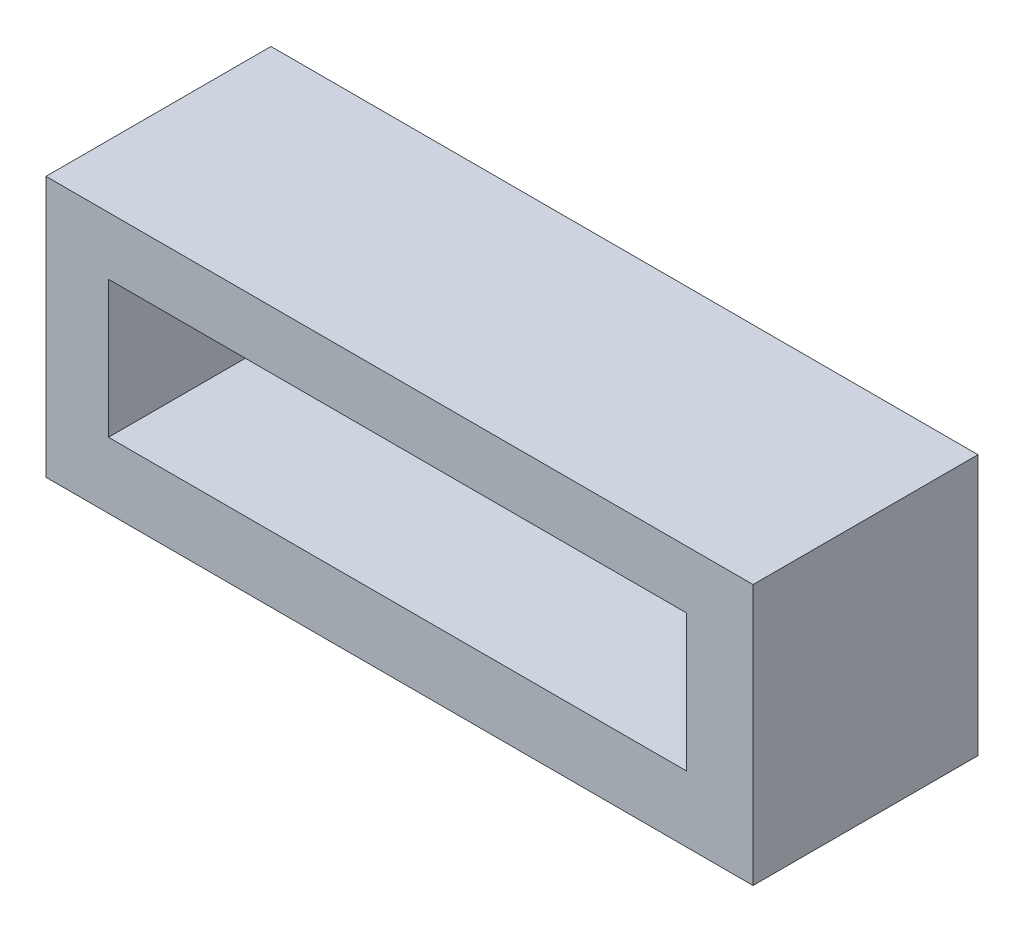
SolidWorks part; units mm, degrees
ref_plane "前基準面" through (0, 0, 0) normal (0, 0, 1) x (1, 0, 0)
ref_plane "上基準面" through (0, 0, 0) normal (0, 1, 0) x (1, 0, 0)
ref_plane "右基準面" through (0, 0, 0) normal (1, 0, 0) x (0, 0, -1)
sketch "草圖1" plane through (0, 0, 0) normal (0, 0, 1) x (1, 0, 0)
  line L1 (-25.4582, 11.8637) -> (24.8318, 11.8637)
  line L2 (-25.4582, 11.8637) -> (-25.4582, -6.6763)
  line L3 (-25.4582, -6.6763) -> (24.8318, -6.6763)
  line L4 (24.8318, 11.8637) -> (24.8318, -6.6763)
  dimension "D1" = 50.29
  dimension "D2" = 18.54
extrude "填料-伸長1" add sketch "草圖1" along normal blind 16
sketch "草圖2" plane through (0, 0, 16) normal (0, 0, 1) x (1, 0, 0)
  line L1 (-21.0124, 7.747) -> (20.0998, 7.747)
  line L2 (-21.0124, 7.747) -> (-21.0124, -1.9871)
  line L3 (-21.0124, -1.9871) -> (20.0998, -1.9871)
  line L4 (20.0998, 7.747) -> (20.0998, -1.9871)
extrude "除料-伸長1" cut sketch "草圖2" against normal blind 10
